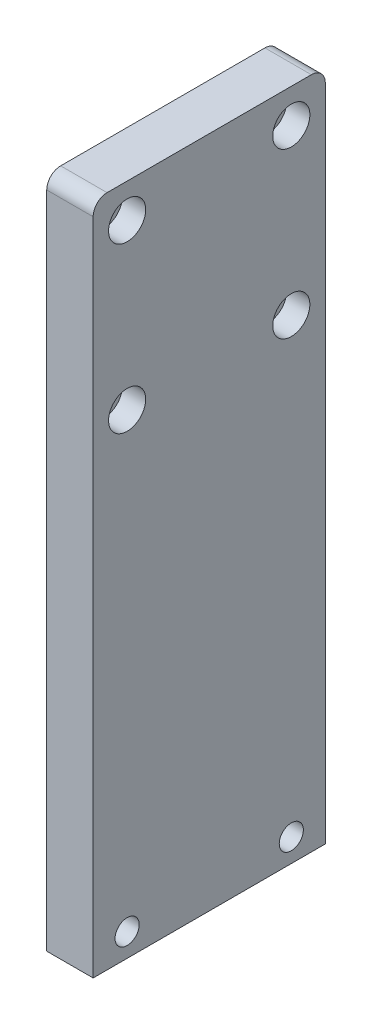
SolidWorks part; units mm, degrees
ref_plane "Alzado" through (0, 0, 0) normal (0, 0, 1) x (1, 0, 0)
ref_plane "Planta" through (0, 0, 0) normal (0, 1, 0) x (1, 0, 0)
ref_plane "Vista lateral" through (0, 0, 0) normal (1, 0, 0) x (0, 0, -1)
sketch "Croquis1" plane through (0, 0, 0) normal (1, 0, 0) x (0, 0, -1)
  line L1 (-25, -120) -> (25, -120)
  line L2 (25, -120) -> (25, 25)
  line L4 (0, 25) -> (0, -120) construction
  line L5 (25, 0) -> (-25, 0) construction
  line L6 (-25, 0) -> (-25, 25)
  line L7 (-25, 0) -> (-25, -120)
  line L8 (-25, 25) -> (0, 25)
  line L9 (0, 25) -> (25, 25)
  line L10 (0, 5.5) -> (0, -5.5) construction
  circle A1 centre (-17.68, 17.68) radius 2.6
  circle A2 centre (17.68, 17.68) radius 2.6
  circle A3 centre (17.68, -17.68) radius 2.6
  circle A4 centre (-17.68, -17.68) radius 2.6
  circle A5 centre (-17.68, -115) radius 2.6
  circle A6 centre (17.68, -115) radius 2.6
  dimension "D7" = 5.2
  dimension "D11" = 5.2
  dimension "D12" = 5.2
  dimension "D13" = 5.2
  dimension "D1" = 25
  dimension "D2" = 25
  dimension "D3" = 17.68
  dimension "D4" = 17.68
  dimension "D5" = 17.68
  dimension "D6" = 120
  dimension "D8" = 17.68
  dimension "D9" = 0
  dimension "D10" = 25
  dimension "D14" = 5
  dimension "D15" = 7.32
extrude "Saliente-Extruir1" add sketch "Croquis1" along normal blind 10
sketch "Croquis5" plane through (10, 0, 0) normal (1, 0, 0) x (0, 0, -1)
  circle A0 centre (17.68, 17.68) radius 4
  circle A1 centre (-17.68, 17.68) radius 4
  circle A2 centre (-17.68, -17.68) radius 4
  circle A3 centre (17.68, -17.68) radius 4
  dimension "D1" = 8
  dimension "D2" = 8
  dimension "D3" = 8
  dimension "D4" = 8
extrude "Cortar-Extruir2" cut sketch "Croquis5" against normal blind 5
fillet "Fillet1" radius 3 2 edges at (5, 25, -25) (5, 25, 25)
sketch "Sketch1" plane through (0, 0, 0) normal (-1, 0, 0) x (0, 0, 1)
  line L0 (0, -5.5) -> (0, 5.5) construction
  circle A0 centre (17.68, -115) radius 4
  circle A2 centre (-17.68, -115) radius 4
  dimension "D1" = 8
extrude "Cut-Extrude1" cut sketch "Sketch1" against normal blind 5
